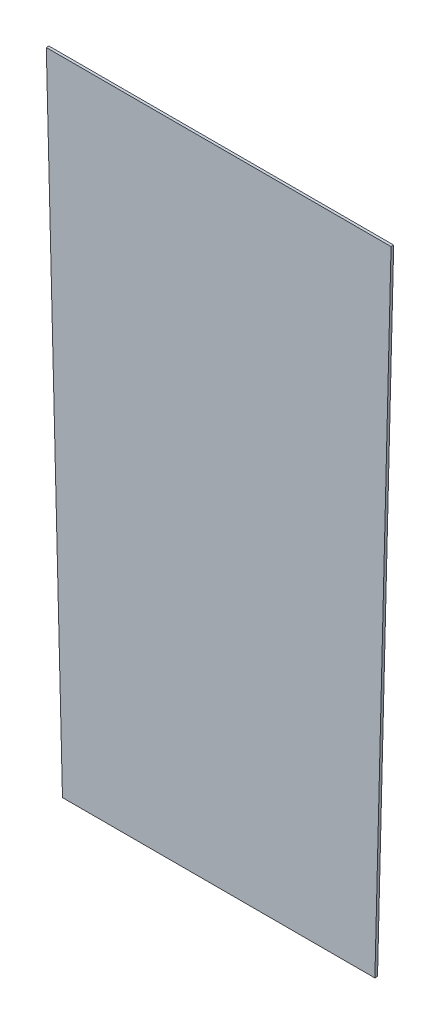
SolidWorks part; units mm, degrees
material "E-Glass Fiber"
ref_plane "Plano frontal" through (0, 0, 0) normal (0, 0, 1) x (1, 0, 0)
ref_plane "Plano superior" through (0, 0, 0) normal (0, 1, 0) x (1, 0, 0)
ref_plane "Plano direito" through (0, 0, 0) normal (1, 0, 0) x (0, 0, -1)
sketch "Sketch1" plane through (0, 0, 0) normal (0, 0, 1) x (1, 0, 0)
  line L0 (78.9183, 45.719) -> (506.4183, 45.719)
  line L1 (506.4183, 45.719) -> (528.5483, 923.589)
  line L2 (528.5483, 923.589) -> (56.7883, 923.589)
  line L3 (56.7883, 923.589) -> (78.9183, 45.719)
  dimension "D1" = 471.76
  dimension "D2" = 427.5
  dimension "D3" = 877.87
  dimension "D4" = 22.13
extrude "Boss-Extrude1" add sketch "Sketch1" along normal blind 3.6
